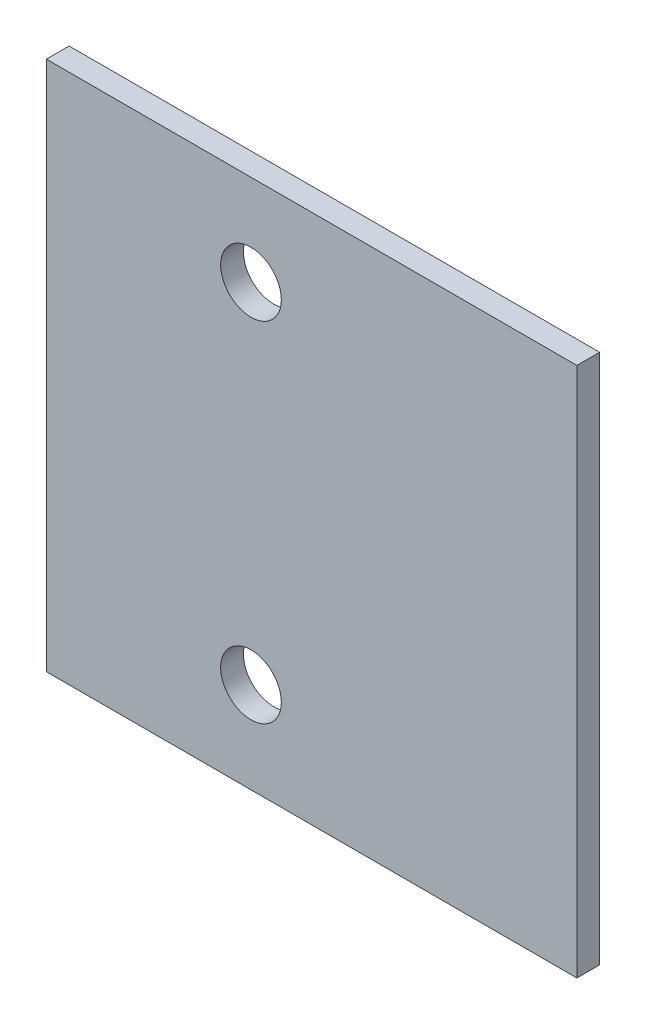
SolidWorks part; units mm, degrees
material "Teak"
ref_plane "Front Plane" through (0, 0, 0) normal (0, 0, 1) x (1, 0, 0)
ref_plane "Top Plane" through (0, 0, 0) normal (0, 1, 0) x (1, 0, 0)
ref_plane "Right Plane" through (0, 0, 0) normal (1, 0, 0) x (0, 0, -1)
sketch "Sketch1" plane through (0, 0, 0) normal (0, 0, 1) x (1, 0, 0)
  line L1 (-35, -35) -> (35, -35)
  line L2 (-35, -35) -> (-35, 35)
  line L3 (-35, 35) -> (35, 35)
  line L4 (35, -35) -> (35, 35)
  line L5 (-35, -35) -> (35, 35) construction
  line L6 (-35, 35) -> (35, -35) construction
  circle A0 centre (-8, -23) radius 4 construction
  circle A1 centre (-8, 23) radius 4 construction
  circle A2 centre (-8, -23) radius 4
  circle A3 centre (-8, 23) radius 4
  point P0 (0, 0)
  dimension "D1" = 70
  dimension "D2" = 70
extrude "Boss-Extrude1" add sketch "Sketch1" along normal mid plane 3
